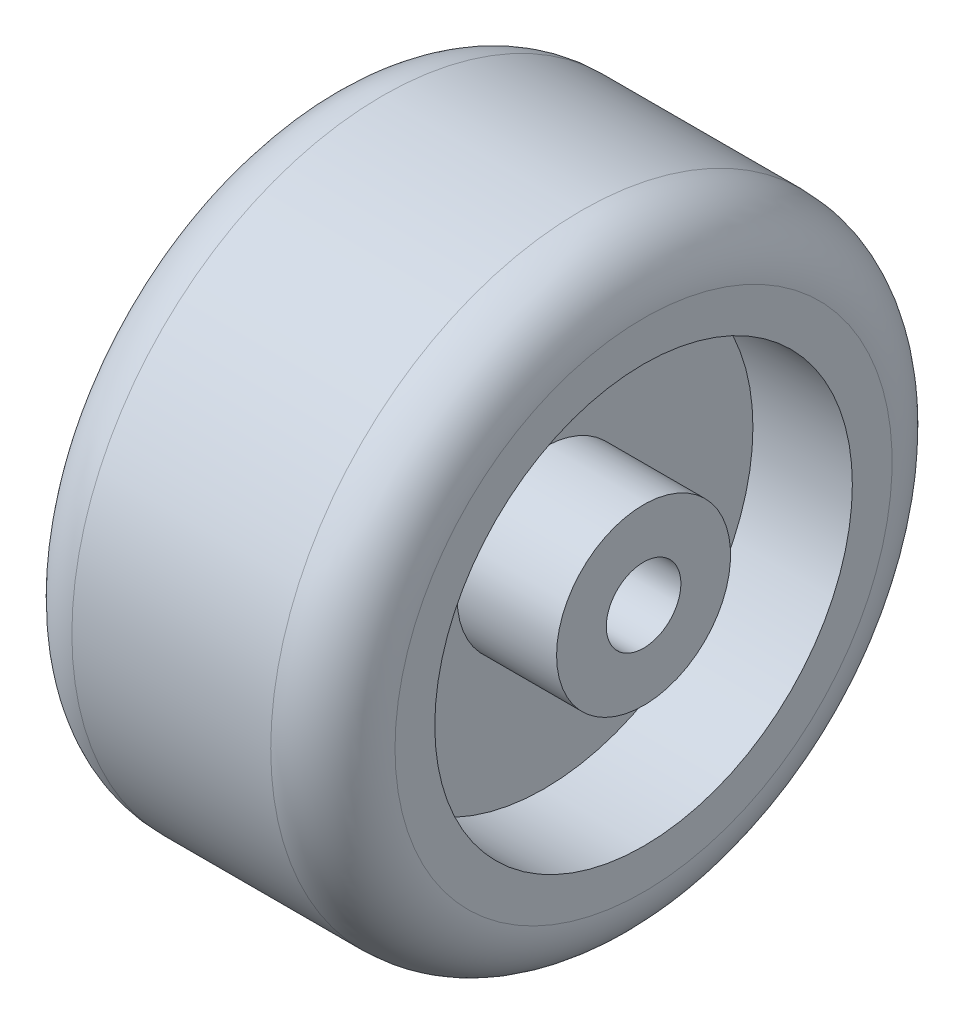
SolidWorks part; units mm, degrees
material "Rubber"
ref_plane "Front Plane" through (0, 0, 0) normal (0, 0, 1) x (1, 0, 0)
ref_plane "Top Plane" through (0, 0, 0) normal (0, 1, 0) x (1, 0, 0)
ref_plane "Right Plane" through (0, 0, 0) normal (1, 0, 0) x (0, 0, -1)
sketch "Sketch1" plane through (0, 0, 0) normal (0, 0, 1) x (1, 0, 0)
  line L0 (0, 1.5) -> (0, 3.5)
  line L1 (0, 3.5) -> (-4, 3.5)
  line L2 (-4, 3.5) -> (-4, 8.4)
  line L3 (-4, 8.4) -> (0, 8.4)
  line L4 (-2.5, 12.5) -> (-10.5, 12.5)
  line L5 (-6.5, -196.8744) -> (-6.5, 9609.4957) construction
  line L6 (0, 8.4) -> (0, 10)
  line L7 (-13, 8.4) -> (-13, 10)
  line L8 (-9, 8.4) -> (-13, 8.4)
  line L9 (-9, 3.5) -> (-9, 8.4)
  line L10 (-13, 3.5) -> (-9, 3.5)
  line L11 (-13, 1.5) -> (-13, 3.5)
  line L12 (-1000.5749, 0) -> (48999.4251, 0) construction
  line L13 (-13, 1.5) -> (0, 1.5)
  arc A0 (0, 10) -> (-2.5, 12.5) centre (-2.5, 10) ccw
  arc A1 (-13, 10) -> (-10.5, 12.5) centre (-10.5, 10) cw
  point P17 (-6.5, 12.5)
  dimension "D5" = 2.5
  dimension "D1" = 6.5
  dimension "D2" = 12.5
  dimension "D3" = 2.5
  dimension "D4" = 1.6
  dimension "D6" = 2
  dimension "D7" = 3
revolve "Revolve1" add sketch "Sketch1" angle 360 about L12
